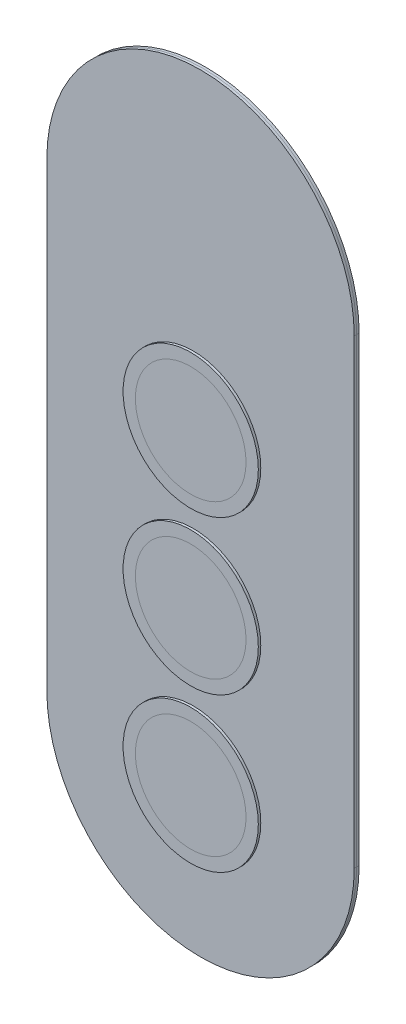
SolidWorks part; units mm, degrees
ref_plane "Front Plane" through (0, 0, 0) normal (0, 0, 1) x (1, 0, 0)
ref_plane "Top Plane" through (0, 0, 0) normal (0, 1, 0) x (1, 0, 0)
ref_plane "Right Plane" through (0, 0, 0) normal (1, 0, 0) x (0, 0, -1)
sketch "Sketch1" plane through (0, 0, 0) normal (0, 0, 1) x (1, 0, 0)
  line L0 (0, -93.75) -> (0, 93.75) construction
  line L1 (-62.5, -93.75) -> (-62.5, 93.75)
  line L2 (62.5, -93.75) -> (62.5, 93.75)
  line L3 (0, 93.75) -> (-62.5, 75.1603) construction
  line L4 (-62.5, 75.1603) -> (-125, 56.5707) construction
  line L5 (-125, 56.5707) -> (-187.5, 37.981) construction
  line L6 (-187.5, 37.981) -> (-250, 19.3913) construction
  line L7 (-250, 19.3913) -> (0, -156.25) construction
  line L8 (-187.5, 37.981) -> (0, -93.75) construction
  line L9 (-125, 56.5707) -> (0, -31.25) construction
  line L10 (-62.5, 75.1603) -> (0, 31.25) construction
  arc A0 (-62.5, -93.75) -> (62.5, -93.75) centre (0, -93.75) ccw
  arc A1 (62.5, 93.75) -> (-62.5, 93.75) centre (0, 93.75) ccw
  circle A2 centre (0, 31.25) radius 25
  circle A3 centre (0, -31.25) radius 25
  circle A4 centre (0, -93.75) radius 25
  point P2 (0, 0)
  dimension "D2" = 50
  dimension "D1" = 125
extrude "Boss-Extrude1" add sketch "Sketch1" along normal blind 1
sketch "Sketch4" plane through (0, 0, 0) normal (0, 0, 1) x (1, 0, 0)
  circle A0 centre (0, -93.75) radius 25 construction
  circle A1 centre (0, -31.25) radius 25 construction
  circle A2 centre (0, 31.25) radius 25 construction
  circle A3 centre (0, -93.75) radius 25 construction
  circle A4 centre (0, -31.25) radius 25 construction
  circle A5 centre (0, 31.25) radius 25 construction
  circle A6 centre (0, 31.25) radius 27.5
  circle A7 centre (0, -31.25) radius 27.5
  circle A8 centre (0, -93.75) radius 27.5
  circle A9 centre (0, 31.25) radius 22.5
  circle A10 centre (0, -31.25) radius 22.5
  circle A11 centre (0, -93.75) radius 22.5
  dimension "D1" = 2.5
  dimension "D2" = 2.5
extrude "Boss-Extrude2" add sketch "Sketch4" along normal blind 1 from offset 5 separate body
sketch "Sketch5" plane through (0, 0, 0) normal (0, 0, 1) x (1, 0, 0)
  circle A0 centre (0, -93.75) radius 22.5 construction
  circle A1 centre (0, -31.25) radius 22.5 construction
  circle A2 centre (0, 31.25) radius 22.5 construction
  circle A3 centre (0, -93.75) radius 22.5
  circle A4 centre (0, -31.25) radius 22.5
  circle A5 centre (0, 31.25) radius 22.5
extrude "Boss-Extrude3" add sketch "Sketch5" along normal blind 1 from offset 5 separate body
sketch "Sketch6" plane through (0, 0, 1) normal (0, 0, 1) x (1, 0, 0)
  line L2 (62.5, -93.75) -> (62.5, 93.75)
  line L3 (-62.5, 93.75) -> (-62.5, -93.75)
  line L4 (62.5, -93.75) -> (62.5, 93.75)
  line L5 (-62.5, 93.75) -> (-62.5, -93.75)
  arc A2 (-62.5, -93.75) -> (62.5, -93.75) centre (0, -93.75) ccw
  arc A3 (62.5, 93.75) -> (-62.5, 93.75) centre (0, 93.75) ccw
  arc A4 (-62.5, -93.75) -> (62.5, -93.75) centre (0, -93.75) ccw
  arc A5 (62.5, 93.75) -> (-62.5, 93.75) centre (0, 93.75) ccw
  dimension "D1" = 0
extrude "Boss-Extrude4" add sketch "Sketch6" along normal blind 1 separate body
